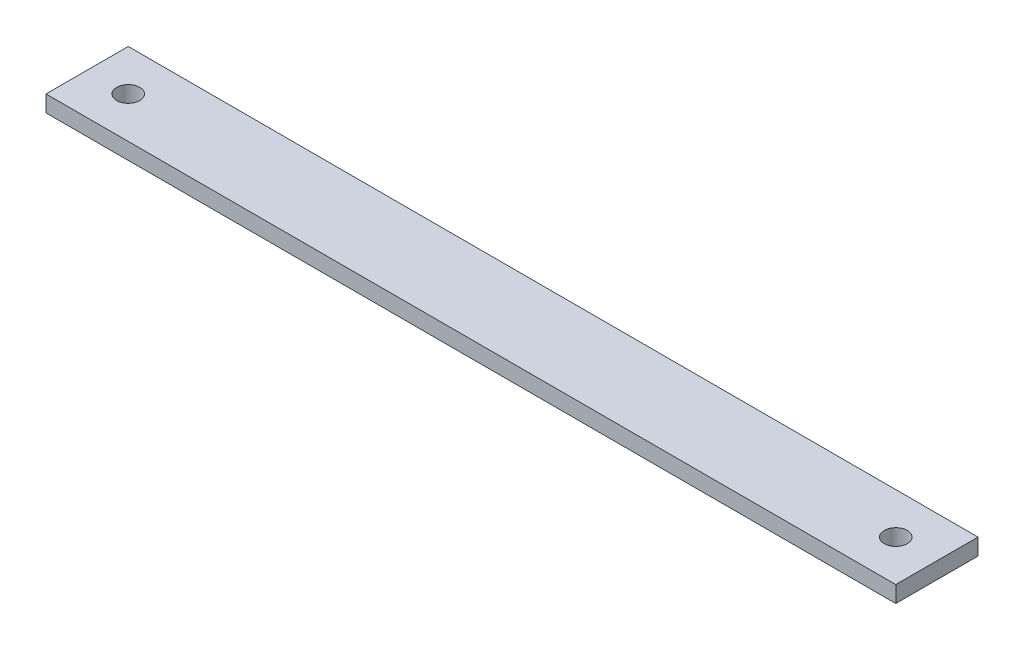
SolidWorks part; units mm, degrees
ref_plane "Front Plane" through (0, 0, 0) normal (0, 0, 1) x (1, 0, 0)
ref_plane "Top Plane" through (0, 0, 0) normal (0, 1, 0) x (1, 0, 0)
ref_plane "Right Plane" through (0, 0, 0) normal (1, 0, 0) x (0, 0, -1)
sketch "Sketch1" plane through (0, 0, 0) normal (0, 1, 0) x (1, 0, 0)
  line L1 (-59.4118, 13.3824) -> (95.5882, 13.3824)
  line L2 (-59.4118, 13.3824) -> (-59.4118, -1.6176)
  line L3 (-59.4118, -1.6176) -> (95.5882, -1.6176)
  line L4 (95.5882, 13.3824) -> (95.5882, -1.6176)
  dimension "D1" = 155
  dimension "D2" = 15
extrude "Boss-Extrude1" add sketch "Sketch1" along normal blind 3
sketch "Sketch2" plane through (0, 3, 0) normal (0, 1, 0) x (1, 0, 0)
  line L0 (-59.4118, 13.3824) -> (-59.4118, -1.6176) construction
  line L1 (95.5882, -1.6176) -> (95.5882, 13.3824) construction
  line L2 (-59.4118, -1.6176) -> (95.5882, -1.6176) construction
  circle A0 centre (-51.9118, 5.8824) radius 2.1
  circle A1 centre (88.0882, 5.8824) radius 2.1
  dimension "D1" = 4.2
  dimension "D2" = 4.2
  dimension "D3" = 7.5
  dimension "D4" = 7.5
  dimension "D5" = 7.5
  dimension "D6" = 7.5
extrude "Cut-Extrude1" cut sketch "Sketch2" against normal blind 3
